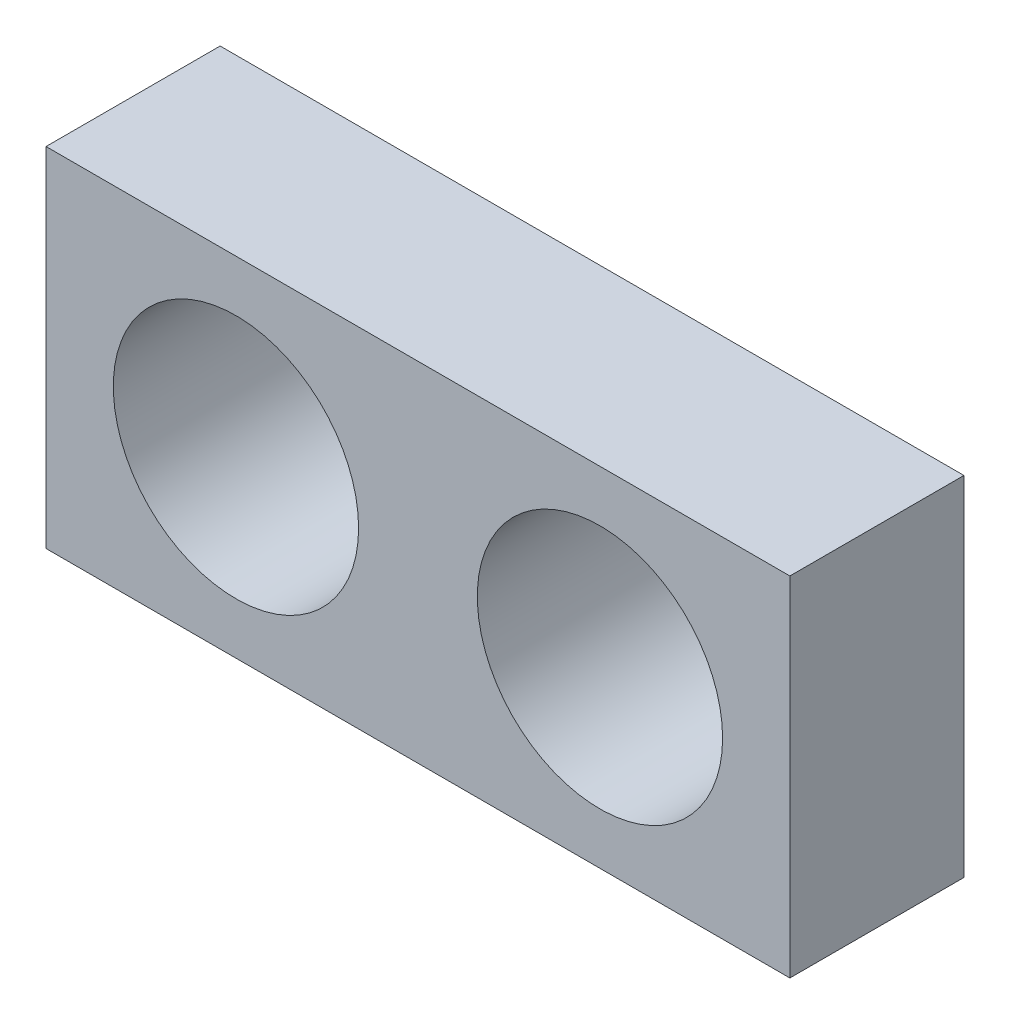
SolidWorks part; units mm, degrees
ref_plane "Front Plane" through (0, 0, 0) normal (0, 0, 1) x (1, 0, 0)
ref_plane "Top Plane" through (0, 0, 0) normal (0, 1, 0) x (1, 0, 0)
ref_plane "Right Plane" through (0, 0, 0) normal (1, 0, 0) x (0, 0, -1)
sketch "Sketch2" plane through (0, 0, 0) normal (0, 0, 1) x (1, 0, 0)
  line L0 (-23.5, 11) -> (-23.5, -11)
  line L1 (-23.5, -11) -> (23.5, -11)
  line L2 (23.5, -11) -> (23.5, 11)
  line L3 (23.5, 11) -> (-23.5, 11)
  point P2 (0, 11)
  point P5 (0, -11)
  point P7 (-23.5, 0)
  point P8 (23.5, 0)
  dimension "D1" = 47
  dimension "D2" = 22
extrude "Boss-Extrude1" add sketch "Sketch2" along normal blind 11
sketch "Sketch3" plane through (0, 0, 11) normal (0, 0, 1) x (1, 0, 0)
  circle A0 centre (-11.5, 0) radius 7.75
  circle A1 centre (11.5, 0) radius 7.75
  dimension "D1" = 15.5
  dimension "D2" = 23
  dimension "D3" = 11.5
extrude "Cut-Extrude1" cut sketch "Sketch3" against normal up to surface (11 mm away) up to face at (0, 0, 0)
